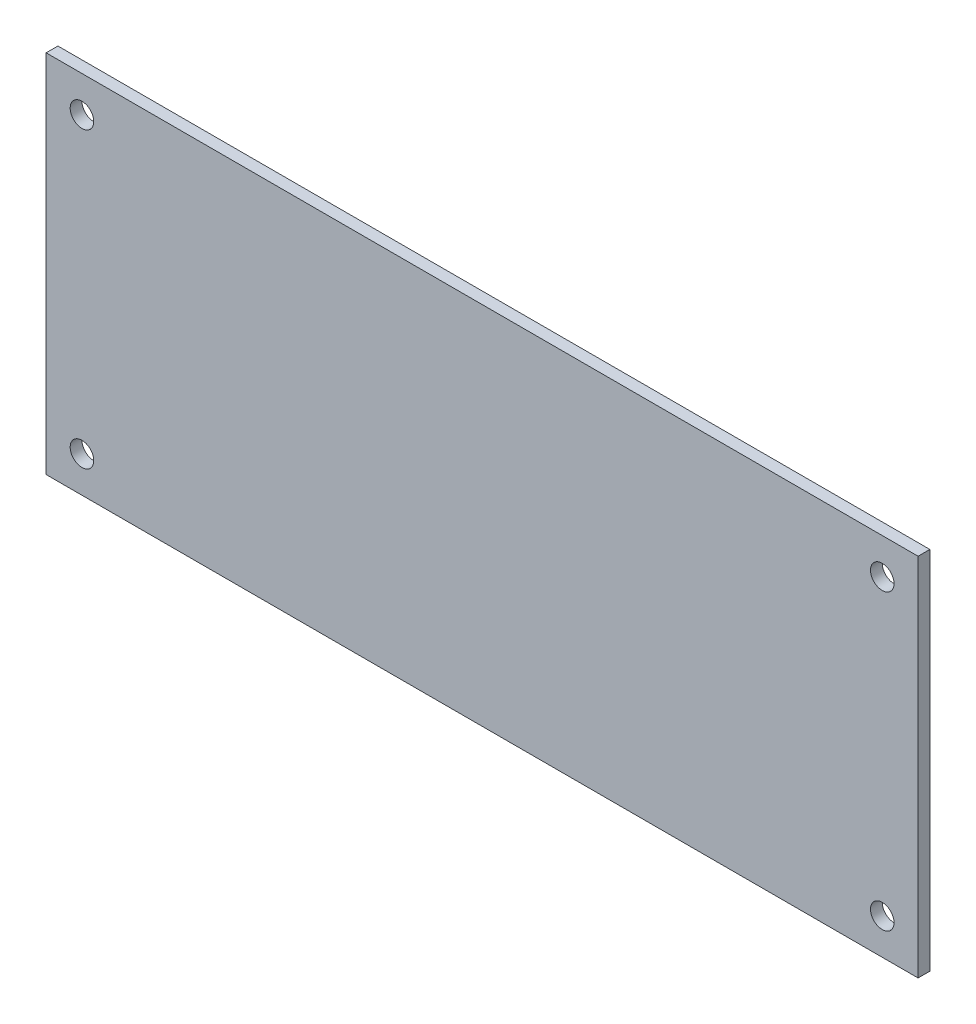
SolidWorks part; units mm, degrees
ref_plane "Front" through (0, 0, 0) normal (0, 0, 1) x (1, 0, 0)
ref_plane "Top" through (0, 0, 0) normal (0, 1, 0) x (1, 0, 0)
ref_plane "Right" through (0, 0, 0) normal (1, 0, 0) x (0, 0, -1)
sketch "Sketch1" plane through (0, 0, 0) normal (0, 0, 1) x (1, 0, 0)
  line L1 (-117.475, -49.2125) -> (117.475, -49.2125)
  line L2 (-117.475, -49.2125) -> (-117.475, 49.2125)
  line L3 (-117.475, 49.2125) -> (117.475, 49.2125)
  line L4 (117.475, -49.2125) -> (117.475, 49.2125)
  line L5 (0, 49.2125) -> (0, -49.2125) construction
  line L6 (-117.475, 0) -> (117.475, 0) construction
  point P0 (0, 0)
  dimension "D1" = 234.95
  dimension "D2" = 98.425
extrude "Boss-Extrude1" add sketch "Sketch1" along normal blind 3.175
sketch "Sketch2" plane through (0, 0, 3.175) normal (0, 0, 1) x (1, 0, 0)
  line L0 (117.475, 49.2125) -> (-117.475, 49.2125) construction
  line L1 (-117.475, 49.2125) -> (-117.475, -49.2125) construction
  line L2 (-117.475, -49.2125) -> (117.475, -49.2125) construction
  line L3 (117.475, -49.2125) -> (117.475, 49.2125) construction
  circle A0 centre (-107.823, 39.5605) radius 3.175
  circle A1 centre (-107.823, -39.5605) radius 3.175
  circle A2 centre (107.823, 39.5605) radius 3.175
  circle A3 centre (107.823, -39.5605) radius 3.175
  dimension "D1" = 6.35
  dimension "D4" = 6.35
  dimension "D7" = 6.35
  dimension "D8" = 9.652
  dimension "D9" = 9.652
  dimension "D2" = 9.652
  dimension "D3" = 9.652
  dimension "D5" = 9.652
  dimension "D6" = 9.652
extrude "Cut-Extrude1" cut sketch "Sketch2" against normal through all
